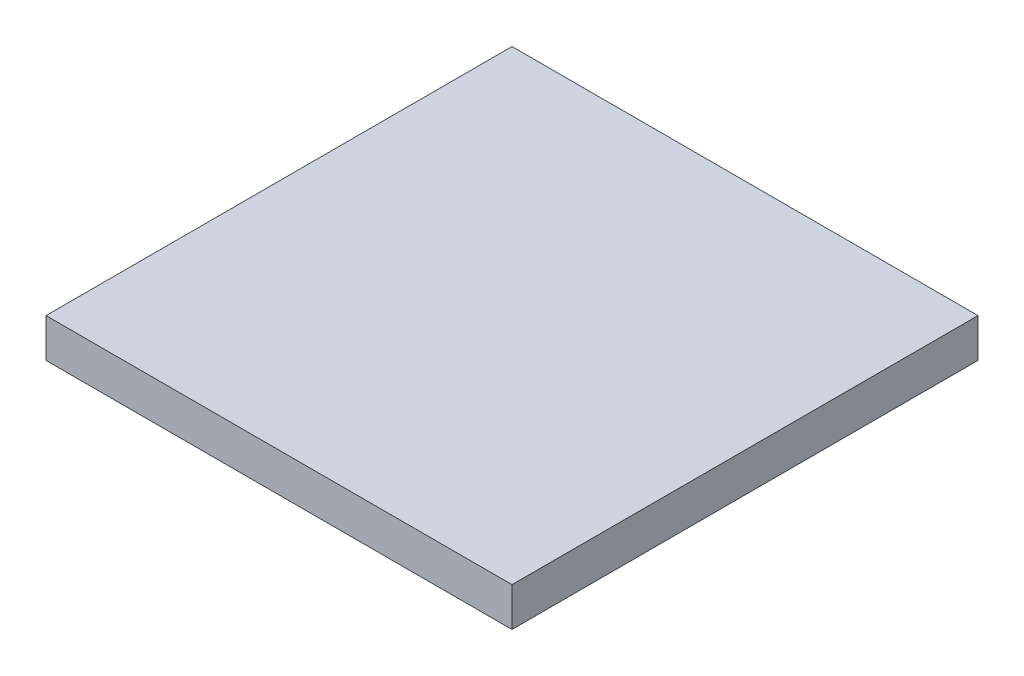
SolidWorks part; units mm, degrees
material "Ceramic Porcelain"
ref_plane "Front Plane" through (0, 0, 0) normal (0, 0, 1) x (1, 0, 0)
ref_plane "Top Plane" through (0, 0, 0) normal (0, 1, 0) x (1, 0, 0)
ref_plane "Right Plane" through (0, 0, 0) normal (1, 0, 0) x (0, 0, -1)
sketch "Sketch1" plane through (0, 0, 0) normal (0, 1, 0) x (1, 0, 0)
  line L0 (-19.05, 19.05) -> (19.05, 19.05)
  line L1 (-19.05, 19.05) -> (-19.05, -19.05)
  line L2 (19.05, 19.05) -> (19.05, -19.05)
  line L3 (-19.05, -19.05) -> (19.05, -19.05)
  line L4 (-19.05, 19.05) -> (19.05, -19.05) construction
  line L5 (19.05, 19.05) -> (-19.05, -19.05) construction
  point P1 (0, 0)
  dimension "D1" = 38.1
  dimension "D2" = 38.1
extrude "Boss-Extrude1" add sketch "Sketch1" along normal blind 3.175
